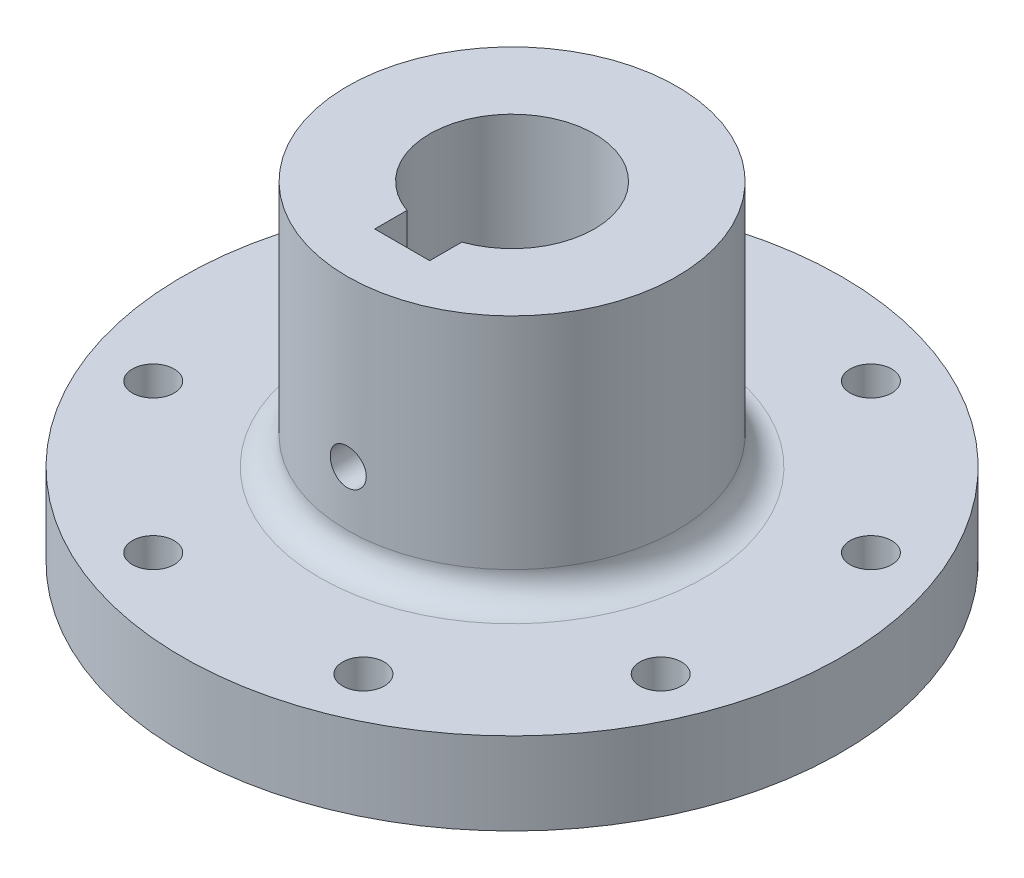
SolidWorks part; units mm, degrees
material "6061-T6 (SS)"
ref_plane "Front Plane" through (0, 0, 0) normal (0, 0, 1) x (1, 0, 0)
ref_plane "Top Plane" through (0, 0, 0) normal (0, 1, 0) x (1, 0, 0)
ref_plane "Right Plane" through (0, 0, 0) normal (1, 0, 0) x (0, 0, -1)
sketch "Sketch1" plane through (0, 0, 0) normal (0, 1, 0) x (1, 0, 0)
  circle A0 centre (0, 0) radius 38.1
  circle A1 centre (0, 0) radius 9.525
  dimension "D1" = 76.2
  dimension "D2" = 19.05
extrude "Boss-Extrude1" add sketch "Sketch1" along normal blind 38.1
hole_wizard "#10-32 Tapped Hole1" positions "Sketch3" profile "Sketch2" tap size "#10-32" standard "Ansi Inch" end condition through all
sketch "Sketch3" plane through (0, 38.1, 0) normal (0, 1, 0) x (-1, 0, 0)
  line L0 (38.1, 0) -> (0, 0) construction
  line L1 (0, 0) -> (29.3332, -12.1502) construction
  circle A0 centre (0, 0) radius 38.1 construction
  point P0 (29.3332, -12.1502)
  dimension "D1" = 31.75
  dimension "D2" = 22.5
sketch "Sketch2" plane through (-29.3332, 38.1, -12.1502) normal (1, 0, 0) x (0, 0, 1)
  line L0 (0, 0) -> (0, 38.1)
  line L1 (0, 38.1) -> (2.413, 38.1)
  line L2 (2.413, 38.1) -> (2.413, 0)
  line L5 (2.413, 0) -> (0, 0)
  line L11 (0, -6.35) -> (0, 107.95) construction
  dimension "Thread Major Dia." = 4.826
  dimension "Thru Tap Drill Depth" = 38.1
pattern_circular "CirPattern1" count 8 over 360 about axis through (0, 0, 0) along (0, 1, 0) of "#10-32 Tapped Hole1"
sketch "Sketch4" plane through (0, 38.1, 0) normal (0, 1, 0) x (1, 0, 0)
  line L1 (-3.175, -12.7) -> (3.175, -12.7)
  line L2 (-3.175, -12.7) -> (-3.175, -6.35)
  line L3 (-3.175, -6.35) -> (3.175, -6.35)
  line L4 (3.175, -12.7) -> (3.175, -6.35)
  line L5 (-3.175, -12.7) -> (3.175, -6.35) construction
  line L6 (-3.175, -6.35) -> (3.175, -12.7) construction
  circle A0 centre (0, 0) radius 9.525 construction
  point P0 (0, -9.525)
  dimension "D1" = 6.35
  dimension "D2" = 6.35
extrude "Cut-Extrude1" cut sketch "Sketch4" against normal through all
hole_wizard "#8-32 Tapped Hole1" positions "Sketch6" profile "Sketch5" tap size "#8-32" standard "ANSI Inch"
sketch "Sketch6" plane through (0, 0, 12.7) normal (0, 0, -1) x (-1, 0, 0)
  line L0 (3.175, 0) -> (-3.175, 0) construction
  line L1 (3.175, 0) -> (3.175, 38.1) construction
  point P0 (0, 19.05)
  dimension "D1" = 19.05
  dimension "D2" = 3.175
sketch "Sketch5" plane through (0, 19.05, 12.7) normal (1, 0, 0) x (0, 1, 0)
  line L0 (0, 0) -> (0, 25.4)
  line L1 (0, 25.4) -> (2.0828, 25.4)
  line L2 (2.0828, 25.4) -> (2.0828, 0)
  line L5 (2.0828, 0) -> (0, 0)
  line L11 (0, -6.35) -> (0, 107.95) construction
  dimension "Thread Major Dia." = 4.1656
  dimension "Thru Tap Drill Depth" = 25.4
sketch "Sketch7" plane through (0, 38.1, 0) normal (0, 1, 0) x (1, 0, 0)
  circle A0 centre (0, 0) radius 19.05
  dimension "D1" = 38.1
extrude "Cut-Extrude2" cut sketch "Sketch7" against normal offset from surface (28.575 mm away) 9.525 flip side to cut up to face at (-29.3332, 0, 14.5632)
fillet "Fillet1" radius 3.175 1 edges at (0, 9.525, 19.05)
